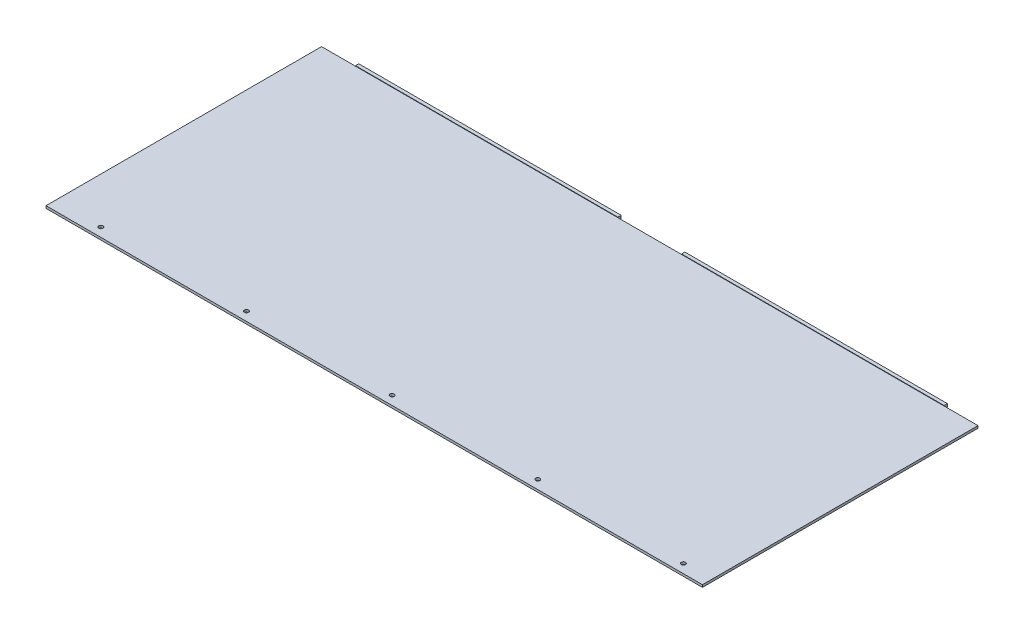
SolidWorks part; units mm, degrees
material "6061-T6 (SS)"
ref_plane "X-Y Datum" through (0, 0, 0) normal (0, 0, 1) x (1, 0, 0)
ref_plane "X-Z Datum" through (0, 0, 0) normal (0, 1, 0) x (1, 0, 0)
ref_plane "Y-Z Datum" through (0, 0, 0) normal (1, 0, 0) x (0, 0, -1)
sketch "Sketch1" plane through (0, 0, 0) normal (0, 1, 0) x (1, 0, 0)
  line L1 (-317.6778, 133.35) -> (317.6778, 133.35)
  line L2 (-317.6778, 133.35) -> (-317.6778, -133.35)
  line L3 (-317.6778, -133.35) -> (317.6778, -133.35)
  line L4 (317.6778, 133.35) -> (317.6778, -133.35)
  line L5 (-317.6778, 133.35) -> (317.6778, -133.35) construction
  line L6 (-317.6778, -133.35) -> (317.6778, 133.35) construction
  point P0 (0, 0)
  dimension "D1" = 635.3556
  dimension "D2" = 266.7
extrude "Boss-Extrude1" add sketch "Sketch1" along normal mid plane 2.286
sketch "Sketch2" plane through (0, 0, -133.35) normal (0, 0, -1) x (-1, 0, 0)
  line L20 (-317.6778, -1.143) -> (317.6778, -1.143) construction
  line L21 (-284.8229, -1.143) -> (-30.8229, -1.143)
  line L22 (30.8229, -1.143) -> (284.8229, -1.143)
  line L40 (30.8229, -1.143) -> (30.8229, 1.5875)
  line L41 (30.8229, 1.5875) -> (284.8229, 1.5875)
  line L42 (284.8229, 1.5875) -> (284.8229, -1.143)
  line L56 (-284.8229, -1.143) -> (-284.8229, 1.5875)
  line L57 (-284.8229, 1.5875) -> (-30.8229, 1.5875)
  line L58 (-30.8229, 1.5875) -> (-30.8229, -1.143)
extrude "Boss-Extrude2" add sketch "Sketch2" along normal blind 3.175
sketch "Sketch3" plane through (0, 1.143, 0) normal (0, 1, 0) x (1, 0, 0)
  line L0 (-273.2278, -133.35) -> (-273.2278, -124.714)
  line L1 (-317.6778, -133.35) -> (317.6778, -133.35) construction
  line L2 (-273.2278, -124.714) -> (-317.6778, -124.714)
  line L3 (-317.6778, 133.35) -> (-317.6778, -133.35) construction
  circle A0 centre (-273.2278, -124.714) radius 2.025
extrude "Cut-Extrude1" cut sketch "Sketch3" against normal blind 10 and the other way blind 10 contours L0 A0 L2 | L2 A0 L0
pattern_linear "LPattern1" count 5 spacing 140.97 along (1, 0, 0) of "Cut-Extrude1"
